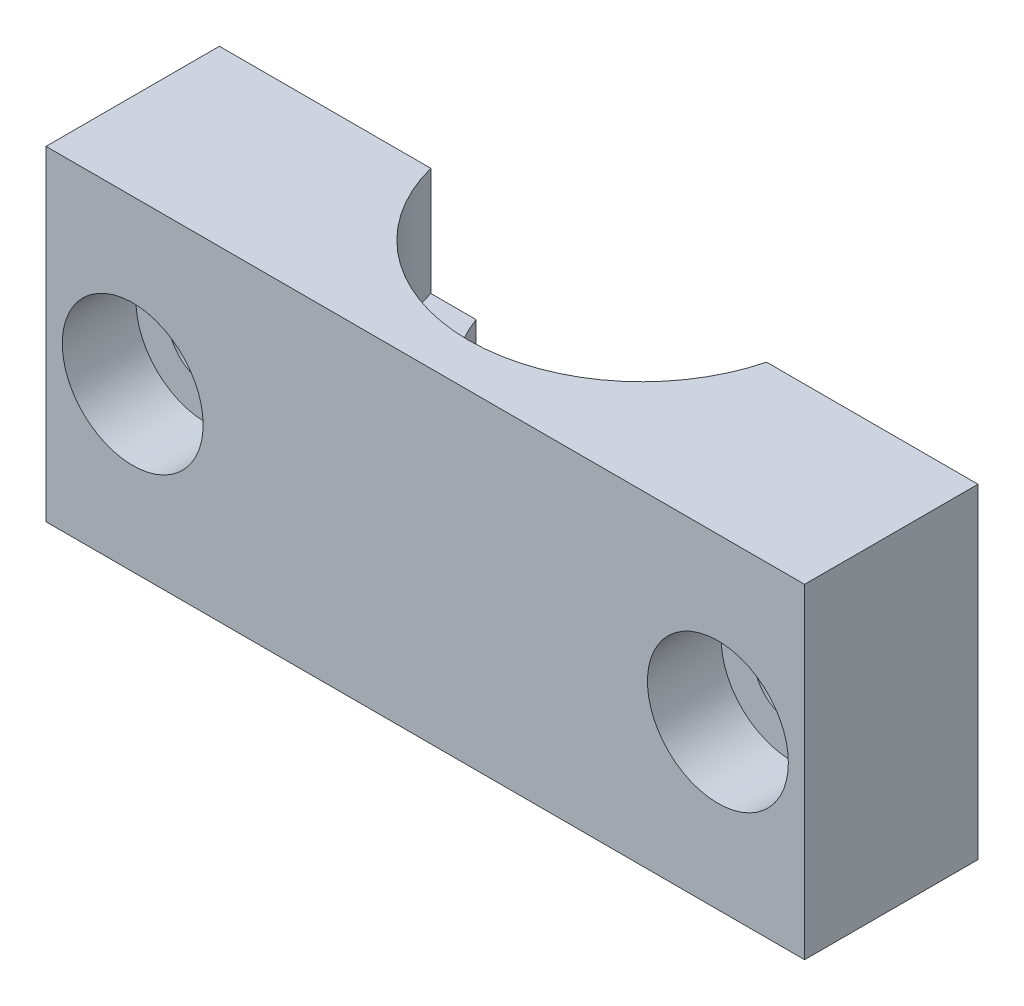
SolidWorks part; units mm, degrees
material "ABS"
ref_plane "Front Plane" through (0, 0, 0) normal (0, 0, 1) x (1, 0, 0)
ref_plane "Top Plane" through (0, 0, 0) normal (0, 1, 0) x (1, 0, 0)
ref_plane "Right Plane" through (0, 0, 0) normal (1, 0, 0) x (0, 0, -1)
sketch "Sketch1" plane through (0, 0, 0) normal (0, 0, 1) x (1, 0, 0)
  line L1 (-17.5, -7.5) -> (17.5, -7.5)
  line L2 (-17.5, -7.5) -> (-17.5, 7.5)
  line L3 (-17.5, 7.5) -> (17.5, 7.5)
  line L4 (17.5, -7.5) -> (17.5, 7.5)
  line L5 (-17.5, -7.5) -> (17.5, 7.5) construction
  line L6 (-17.5, 7.5) -> (17.5, -7.5) construction
  point P0 (0, 0)
  dimension "D1" = 35
  dimension "D2" = 15
extrude "Boss-Extrude1" add sketch "Sketch1" along normal blind 10
sketch "Sketch2" plane through (0, 0, 0) normal (0, 0, -1) x (-1, 0, 0)
  line L0 (0, 7.5) -> (0, -7.5) construction
  line L1 (-17.5, 7.5) -> (17.5, 7.5) construction
  line L2 (17.5, -7.5) -> (-17.5, -7.5) construction
  line L3 (0, 7.5) -> (8, 7.5)
  line L4 (8, 7.5) -> (8, 2.5)
  line L5 (8, 2.5) -> (6, 2.5)
  line L6 (6, 2.5) -> (6, -3.5)
  line L7 (6, -3.5) -> (8, -3.5)
  line L8 (8, -3.5) -> (8, -7.5)
  line L9 (8, -7.5) -> (0, -7.5)
  line L10 (0, 7.5) -> (0, -7.5)
  dimension "D1" = 8
  dimension "D2" = 5
  dimension "D3" = 2
  dimension "D4" = 6
revolve "Cut-Revolve1" cut sketch "Sketch2" angle 180 about L0
sketch "Sketch3" plane through (0, 0, 10) normal (0, 0, 1) x (1, 0, 0)
  line L0 (17.5, 7.5) -> (-17.5, 7.5) construction
  line L2 (-8, 2.5) -> (-8, 7.5) construction
  line L3 (8, 2.5) -> (8, 7.5) construction
  circle A0 centre (-13.5, 0) radius 1.75
  circle A1 centre (13.5, 0) radius 1.75
  dimension "D1" = 3.5
  dimension "D4" = 3.5
  dimension "D2" = 7.5
  dimension "D3" = 5.5
  dimension "D5" = 5.5
extrude "Cut-Extrude1" cut sketch "Sketch3" against normal through all
hole_wizard "CBORE for M3 Hex Socket Head Cap Screw1" positions "Sketch4" profile "Sketch5" counterbore size "M3" standard "ISO" end condition through all
sketch "Sketch4" plane through (0, 0, 10) normal (0, 0, 1) x (1, 0, 0)
  point P0 (-13.5, 0)
  point P3 (13.5, 0)
sketch "Sketch5" plane through (-13.5, 0, 10) normal (1, 0, 0) x (0, -1, 0)
  line L0 (0, 0) -> (0, 10)
  line L1 (0, 10) -> (1.7, 10)
  line L3 (1.7, 10) -> (1.7, 3.4)
  line L4 (1.7, 3.4) -> (3.25, 3.4)
  line L5 (3.25, 3.4) -> (3.25, 0)
  line L7 (3.25, 0) -> (0, 0)
  line L11 (0, -6.35) -> (0, 107.95) construction
  dimension "Thru Hole Dia." = 3.4
  dimension "Thru Hole Depth" = 10
  dimension "C'Bore Dia." = 6.5
  dimension "C'Bore Depth" = 3.4
sketch "Sketch6" plane through (0, 7.5, 0) normal (0, 1, 0) x (1, 0, 0)
  line L0 (-17.5, -10) -> (-17.5, 0) construction
  line L1 (17.5, 2) -> (-17.5, 2)
  line L2 (17.5, 2) -> (17.5, -2)
  line L3 (17.5, -2) -> (-17.5, -2)
  line L4 (-17.5, 2) -> (-17.5, -2)
  line L5 (17.5, 2) -> (-17.5, -2) construction
  line L6 (17.5, -2) -> (-17.5, 2) construction
  point P0 (0, 0)
  dimension "D1" = 4
extrude "Cut-Extrude2" cut sketch "Sketch6" against normal through all
